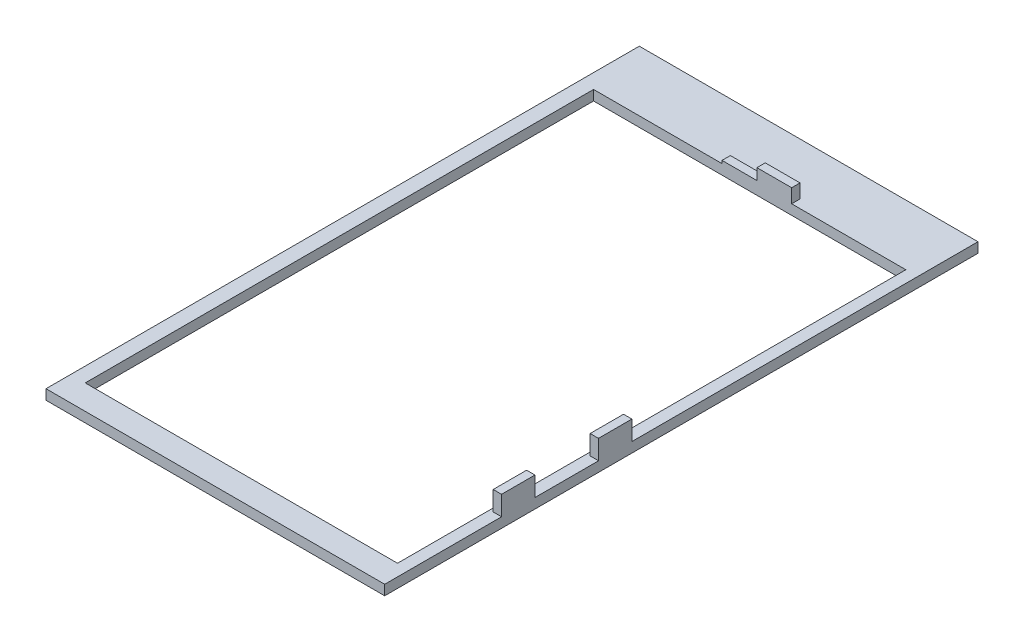
SolidWorks part; units mm, degrees
ref_plane "Front Plane" through (0, 0, 0) normal (0, 0, 1) x (1, 0, 0)
ref_plane "Top Plane" through (0, 0, 0) normal (0, 1, 0) x (1, 0, 0)
ref_plane "Right Plane" through (0, 0, 0) normal (1, 0, 0) x (0, 0, -1)
sketch "Sketch1" plane through (0, 0, 0) normal (0, 1, 0) x (1, 0, 0)
  line L0 (26.2481, 14.4067) -> (26.2382, 20.9067) construction
  line L1 (4.7511, 20.874) -> (16.7382, 20.8922) construction
  line L2 (-0.3474, -87.1339) -> (-0.3459, -88.1339) construction
  line L3 (26.2481, 14.4067) -> (16.7481, 14.3922) construction
  line L4 (26.2481, 14.4067) -> (-0.0019, 14.3667) construction
  line L5 (24.2864, -1.2339) -> (28.4864, -1.2339) construction
  line L6 (26.4026, -87.0932) -> (-27.0974, -87.1746) construction
  line L7 (-27.0974, -87.1746) -> (-27.2518, 14.3252) construction
  line L8 (-27.2518, 14.3252) -> (-0.0019, 14.3667) construction
  line L9 (16.7481, 14.3922) -> (16.7382, 20.8922) construction
  line L10 (4.7614, 14.1135) -> (4.7511, 20.874) construction
  line L16 (-0.3459, -88.1339) -> (29.1041, -88.1339)
  line L22 (29.1041, -88.1339) -> (29.1041, 15.3661)
  line L23 (-0.3459, -88.1339) -> (-28.6959, -88.1339)
  line L24 (-28.6959, -88.1339) -> (-28.6959, 15.3661)
  line L25 (-28.6959, 15.3661) -> (29.1041, 15.3661)
  line L26 (-0.3459, -88.1339) -> (-0.3436, -89.6339) construction
  line L27 (-0.3436, -89.6339) -> (-30.1936, -89.6339)
  line L28 (-0.3436, -89.6339) -> (30.6064, -89.6339)
  line L29 (30.6064, -89.6339) -> (30.6064, 16.8661)
  line L30 (-30.1936, -89.6339) -> (-30.1936, 16.8661)
  line L31 (-30.1936, 16.8661) -> (30.6064, 16.8661)
  line L32 (-23.9736, 0.0361) -> (-23.9736, 6.0361) construction
  line L33 (28.4864, -1.2339) -> (28.4864, 7.1545) construction
  line L34 (-23.9736, 0.0361) -> (-27.5736, 0.0361) construction
  line L35 (-23.9736, 6.0361) -> (28.4864, 6.0361) construction
  line L37 (-27.5736, 6.0361) -> (-23.9736, 6.0361) construction
  line L39 (-27.5736, 6.0361) -> (28.4864, 6.0361)
  line L40 (28.4864, 6.0361) -> (28.4864, -85.2139)
  line L42 (-23.9736, -82.5139) -> (-23.9736, -85.2139) construction
  line L44 (-23.9736, -82.5139) -> (-27.5736, -82.5139) construction
  line L49 (-27.5736, -85.2139) -> (28.4864, -85.2139)
  line L50 (-27.5736, 6.0361) -> (-27.5736, -85.2139)
  circle A8 centre (-23.9736, -82.5139) radius 1.6
  circle A9 centre (24.2864, -76.1639) radius 1.6
  circle A10 centre (24.2864, -1.2339) radius 1.6
  circle A11 centre (-23.9736, 0.0361) radius 1.6
  dimension "D3" = 6
  dimension "D4" = 3.6
  dimension "D6" = 2.7
  dimension "D5" = 4.2
  dimension "D7" = 3.6
  dimension "D9" = 101.5
  dimension "D10" = 53.5
  dimension "D12" = 6.5
  dimension "D13" = 9.5
  dimension "D14" = 1
  dimension "D15" = 29.45
  dimension "D16" = 103.5
  dimension "D17" = 28.35
  dimension "D18" = 1.5
  dimension "D19" = 29.85
  dimension "D20" = 30.95
  dimension "D21" = 106.5
  dimension "D22" = 26.75
extrude "Boss-Extrude1" add sketch "Sketch1" along normal blind 1.8
sketch "Sketch4" plane through (0, 0, -6.0361) normal (0, 0, 1) x (1, 0, 0)
  line L0 (7.9864, 1.8) -> (7.9864, 4.3)
  line L1 (30.6064, 1.8) -> (-30.1936, 1.8) construction
  line L2 (7.9864, 7.3) -> (7.9864, 1.8) construction
  line L3 (1.7497, 4.3) -> (1.7497, 2.3)
  line L4 (1.7497, 4.3) -> (7.9864, 4.3)
  line L5 (1.7497, 1.8) -> (7.9864, 1.8)
  line L6 (-4.5013, 1.8) -> (-4.5136, 2.3)
  line L7 (-4.5136, 5.5) -> (-4.5136, 1.8) construction
  line L8 (-4.5136, 2.3) -> (1.7497, 2.3)
  line L9 (-4.5013, 1.8) -> (1.7497, 1.8)
  dimension "D1" = 2.5
  dimension "D2" = 0.5
extrude "Boss-Extrude2" add sketch "Sketch4" against normal blind 1.5
sketch "Sketch5" plane through (30.6064, 0, 0) normal (1, 0, 0) x (0, 0, -1)
  line L0 (-68.6574, 1.8) -> (-68.6639, 5.3)
  line L1 (-89.6339, 1.8) -> (16.8661, 1.8) construction
  line L2 (-68.6639, 5.5) -> (-68.6639, 1.8) construction
  line L3 (-68.6639, 5.3) -> (-62.6639, 5.3)
  line L4 (-62.6639, 5.5) -> (-62.6639, 1.8) construction
  line L5 (-62.6639, 5.3) -> (-62.6639, 1.8)
  line L6 (-62.6639, 1.8) -> (-68.6574, 1.8)
  line L7 (-51.2437, 1.8) -> (-51.2639, 5.3)
  line L8 (-51.2639, 5.5) -> (-51.2639, 1.8) construction
  line L9 (-51.2639, 5.3) -> (-45.2639, 5.3)
  line L10 (-45.2639, 8.8) -> (-45.2639, 1.8) construction
  line L11 (-45.2639, 5.3) -> (-45.2639, 1.8)
  line L12 (-45.2639, 1.8) -> (-51.2437, 1.8)
  dimension "D1" = 3.5
extrude "Boss-Extrude3" add sketch "Sketch5" against normal blind 1.5
